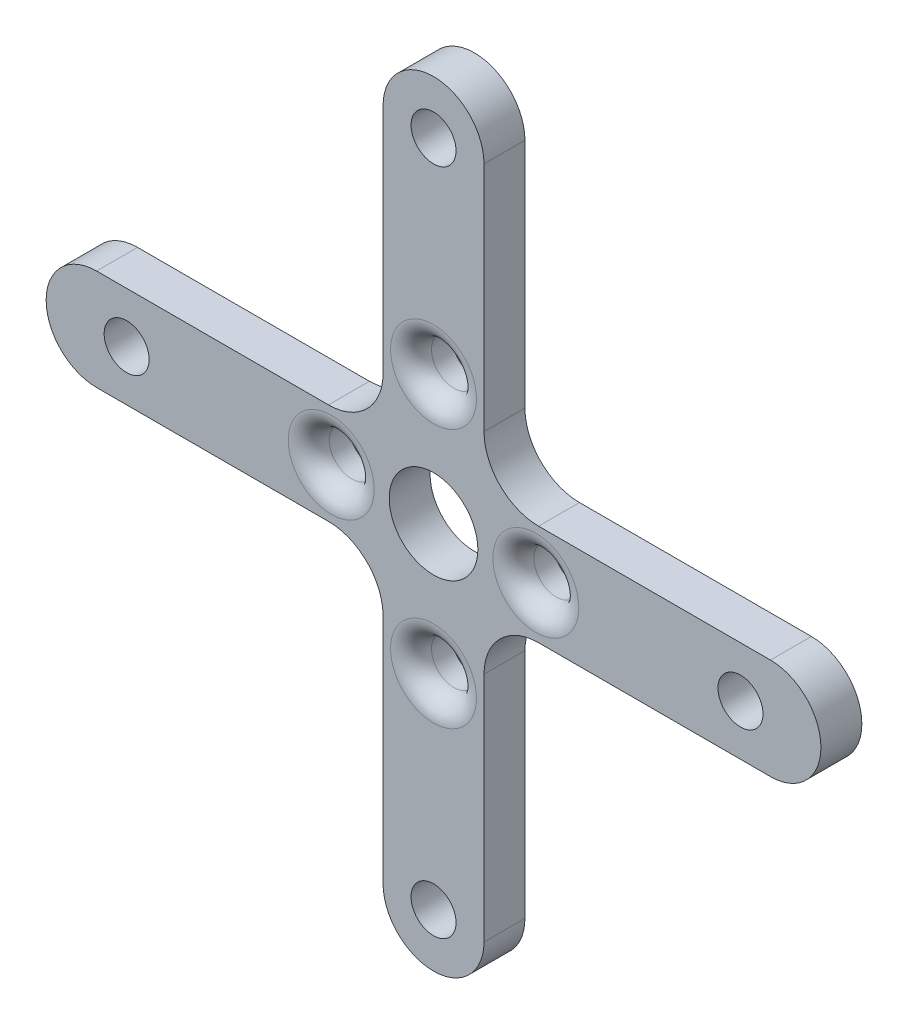
SolidWorks part; units mm, degrees
ref_plane "Alzado" through (0, 0, 0) normal (0, 0, 1) x (1, 0, 0)
ref_plane "Planta" through (0, 0, 0) normal (0, 1, 0) x (1, 0, 0)
ref_plane "Vista lateral" through (0, 0, 0) normal (1, 0, 0) x (0, 0, -1)
sketch "Croquis1" plane through (0, 0, 0) normal (0, 0, 1) x (1, 0, 0)
  line L9 (-7.7, 3.7) -> (-24.7, 3.7)
  line L10 (-7.7, -3.7) -> (-24.7, -3.7)
  line L12 (-3.7, -7.7) -> (-3.7, -24.7)
  line L13 (3.7, -7.7) -> (3.7, -24.7)
  line L15 (7.7, -3.7) -> (24.7, -3.7)
  line L16 (7.7, 3.7) -> (24.7, 3.7)
  line L18 (-3.7, 7.7) -> (-3.7, 24.7)
  line L19 (3.7, 7.7) -> (3.7, 24.7)
  circle A0 centre (0, 0) radius 5
  circle A1 centre (0, 7.7) radius 1.65
  circle A2 centre (0, -7.7) radius 1.65
  circle A3 centre (7.7, 0) radius 1.65
  circle A4 centre (-7.7, 0) radius 1.65
  circle A5 centre (-17.7, 0) radius 1.65
  circle A6 centre (17.7, 0) radius 1.65
  circle A7 centre (0, -17.7) radius 1.65
  circle A8 centre (0, 17.7) radius 1.65
  arc A9 (-7.7, 3.7) -> (-3.7, 7.7) centre (-7.7, 7.7) ccw
  arc A10 (3.7, 7.7) -> (7.7, 3.7) centre (7.7, 7.7) ccw
  arc A11 (-3.7, -7.7) -> (-7.7, -3.7) centre (-7.7, -7.7) ccw
  arc A12 (7.7, -3.7) -> (3.7, -7.7) centre (7.7, -7.7) ccw
  arc A13 (3.7, 24.7) -> (-3.7, 24.7) centre (0, 24.7) ccw
  arc A14 (-3.7, -24.7) -> (3.7, -24.7) centre (0, -24.7) ccw
  arc A16 (-24.7, 3.7) -> (-24.7, -3.7) centre (-24.7, 0) ccw
  arc A17 (24.7, -3.7) -> (24.7, 3.7) centre (24.7, 0) ccw
  circle A18 centre (-17.7, 0) radius 1.65
  dimension "D1" = 10
  dimension "D2" = 3.3
  dimension "D3" = 3.3
  dimension "D4" = 3.3
  dimension "D5" = 3.3
  dimension "D6" = 3.3
  dimension "D7" = 3.3
  dimension "D8" = 3.3
  dimension "D9" = 3.3
  dimension "D11" = 7.7
  dimension "D10" = 10
  dimension "D12" = 7.7
  dimension "D13" = 7.7
  dimension "D14" = 7.7
  dimension "D15" = 10
  dimension "D16" = 10
  dimension "D17" = 10
  dimension "D26" = 17
  dimension "D27" = 17
  dimension "D28" = 17
  dimension "D29" = 17
extrude "Saliente-Extruir2" add sketch "Croquis1" along normal blind 3 contours L15 A17 L16 A10 L19 A13 L18 A9 L9 A16 L10 A11 L12 A14 L13 A12
sketch "Croquis3" plane through (0, 0, 3) normal (0, 0, 1) x (1, 0, 0)
  line L0 (-7.5, 0) -> (-22.5, 0) construction
  line L1 (0, 9.5) -> (0, 24.5) construction
  line L2 (7.5, 0) -> (22.5, 0) construction
  line L3 (0, -9.5) -> (0, -24.5) construction
  circle A1 centre (0, 0) radius 3.25
  circle A2 centre (-7.5, 0) radius 1.65
  circle A3 centre (-22.5, 0) radius 1.65
  circle A4 centre (0, -9.5) radius 1.65
  circle A5 centre (7.5, 0) radius 1.65
  circle A6 centre (0, 9.5) radius 1.65
  circle A7 centre (0, 24.5) radius 1.65
  circle A8 centre (22.5, 0) radius 1.65
  circle A9 centre (0, -24.5) radius 1.65
  dimension "D1" = 6.5
  dimension "D3" = 3.3
  dimension "D5" = 3.3
  dimension "D6" = 3.3
  dimension "D7" = 3.3
  dimension "D8" = 3.3
  dimension "D15" = 3.3
  dimension "D16" = 3.3
  dimension "D17" = 3.3
  dimension "D2" = 7.5
  dimension "D4" = 15
  dimension "D9" = 9.5
  dimension "D10" = 7.5
  dimension "D11" = 9.5
  dimension "D12" = 15
  dimension "D13" = 15
  dimension "D14" = 15
extrude "Cortar-Extruir1" cut sketch "Croquis3" against normal blind 3
fillet "Redondeo1" radius 1.5 1 edges at (-5.85, 0, 3)
fillet "Redondeo2" radius 1.5 1 edges at (1.65, 9.5, 3)
fillet "Redondeo3" radius 1.5 1 edges at (9.15, 0, 3)
fillet "Redondeo4" radius 1.5 1 edges at (1.65, -9.5, 3)
